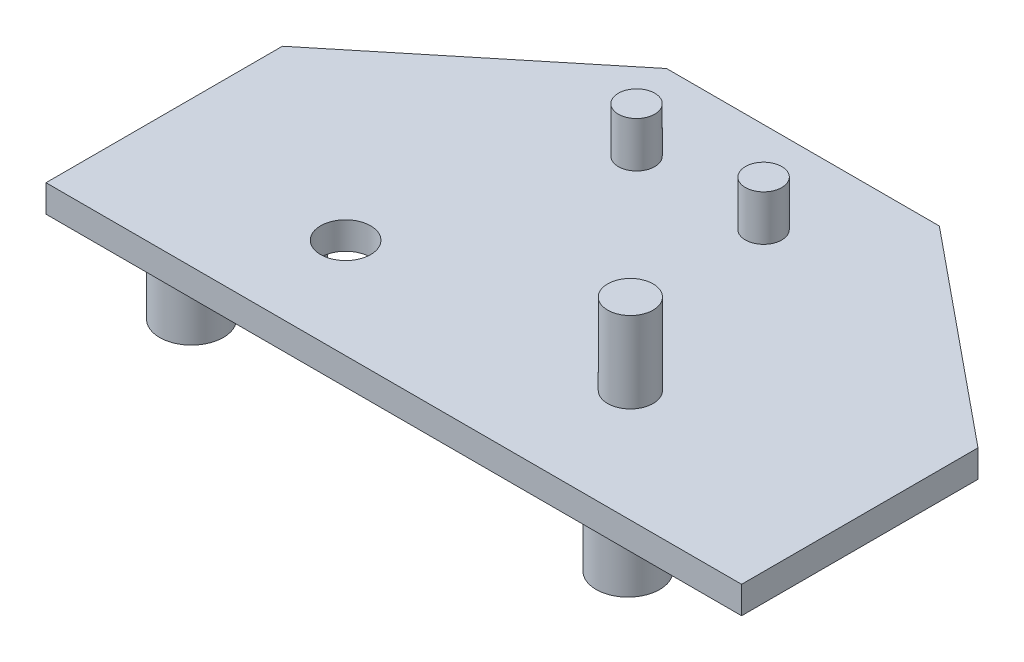
SolidWorks part; units mm, degrees
material "ABS"
ref_plane "Front Plane" through (0, 0, 0) normal (0, 0, 1) x (1, 0, 0)
ref_plane "Top Plane" through (0, 0, 0) normal (0, 1, 0) x (1, 0, 0)
ref_plane "Right Plane" through (0, 0, 0) normal (1, 0, 0) x (0, 0, -1)
sketch "Sketch1" plane through (0, 0, 0) normal (0, 1, 0) x (1, 0, 0)
  circle A0 centre (0, 0) radius 1.5
  circle A1 centre (48, 0) radius 1.5
  circle A2 centre (0, -10) radius 1.5
  circle A3 centre (48, -10) radius 1.5
  circle A4 centre (0, 0) radius 3.5
  circle A5 centre (0, -10) radius 3.5
  circle A6 centre (48, -10) radius 3.5
  circle A7 centre (48, 0) radius 3.5
  dimension "D1" = 3
  dimension "D4" = 7
  dimension "D2" = 48
  dimension "D3" = 10
extrude "Boss-Extrude1" add sketch "Sketch1" along normal blind 10
sketch "Sketch2" plane through (0, 10, 0) normal (0, 1, 0) x (1, 0, 0)
  line L0 (-8, -18) -> (-8, 8)
  line L1 (-8, 8) -> (15.25, 27)
  line L2 (15.25, 27) -> (45.25, 27)
  line L3 (45.25, 27) -> (68.5, 8)
  line L4 (68.5, 8) -> (68.5, -18)
  line L5 (68.5, -18) -> (-8, -18)
  circle A0 centre (48, 0) radius 1.5 construction
  circle A1 centre (48, -10) radius 1.5 construction
  dimension "D1" = 8
  dimension "D2" = 20.5
  dimension "D3" = 8
  dimension "D4" = 30
  dimension "D5" = 45
  dimension "D6" = 8
extrude "Boss-Extrude2" add sketch "Sketch2" along normal blind 3
sketch "Sketch3" plane through (0, 10, 0) normal (0, -1, 0) x (1, 0, 0)
  circle A0 centre (13.95, 7) radius 2.75
  dimension "D3" = 5.5
  dimension "D1" = 13.95
  dimension "D2" = 7
extrude "Cut-Extrude1" cut sketch "Sketch3" against normal blind 4
sketch "Sketch4" plane through (0, 13, 0) normal (0, 1, 0) x (1, 0, 0)
  circle A0 centre (43.9196, -5.65) radius 2.5
  circle A4 centre (13.95, -7) radius 2.75 construction
  dimension "D2" = 5
  dimension "D3" = 30
  dimension "D1" = 5.65
extrude "Boss-Extrude3" add sketch "Sketch4" along normal blind 8.9 contours A0
sketch "Sketch5" plane through (0, 13, 0) normal (0, 1, 0) x (1, 0, 0)
  circle A0 centre (21.95, 17) radius 2
  circle A1 centre (35.9196, 17) radius 2
  circle A2 centre (13.95, -7) radius 2.75 construction
  circle A3 centre (43.9196, -5.65) radius 2.5 construction
  dimension "D1" = 4
  dimension "D2" = 4
  dimension "D3" = 24
  dimension "D4" = 8
  dimension "D5" = 8
extrude "Boss-Extrude4" add sketch "Sketch5" along normal blind 5
